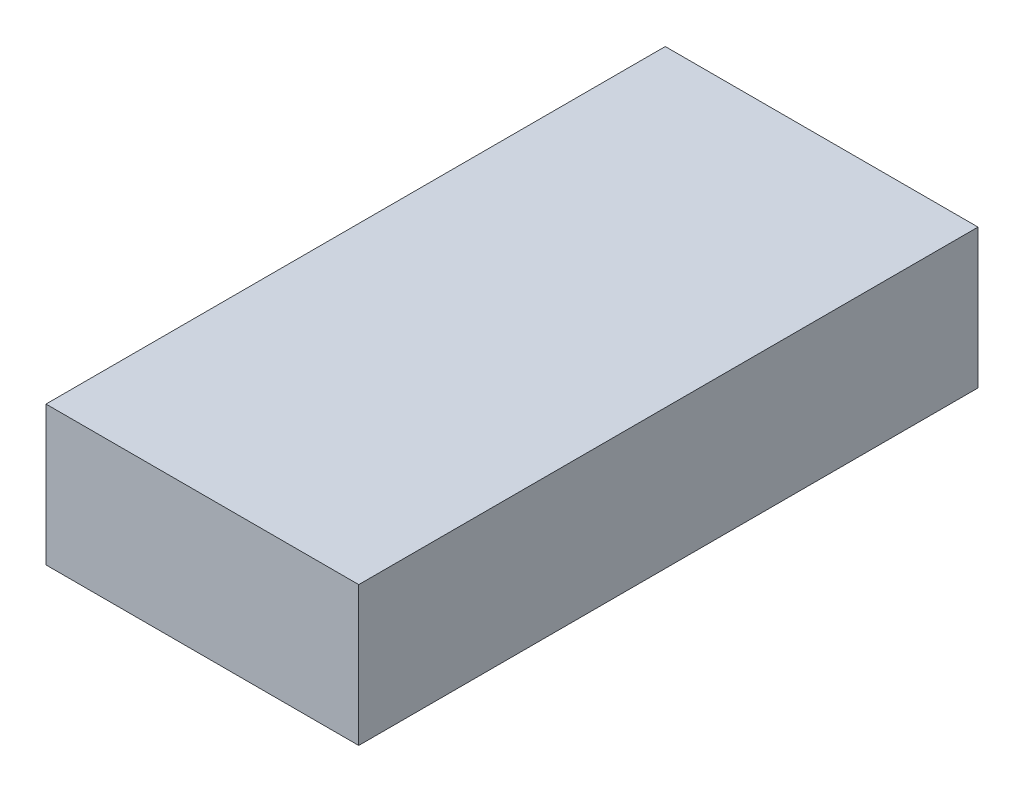
SolidWorks part; units mm, degrees
ref_plane "Спереди" through (0, 0, 0) normal (0, 0, 1) x (1, 0, 0)
ref_plane "Сверху" through (0, 0, 0) normal (0, 1, 0) x (1, 0, 0)
ref_plane "Справа" through (0, 0, 0) normal (1, 0, 0) x (0, 0, -1)
sketch "Эскиз1" plane through (0, 0, 0) normal (0, 1, 0) x (1, 0, 0)
  line L1 (-10.1, 20) -> (10.1, 20)
  line L2 (-10.1, 20) -> (-10.1, -20)
  line L3 (-10.1, -20) -> (10.1, -20)
  line L4 (10.1, 20) -> (10.1, -20)
  line L5 (-10.1, 20) -> (10.1, -20) construction
  line L6 (-10.1, -20) -> (10.1, 20) construction
  point P0 (0, 0)
  dimension "D1" = 20.2
  dimension "D2" = 40
extrude "Бобышка-Вытянуть1" add sketch "Эскиз1" along normal blind 9
